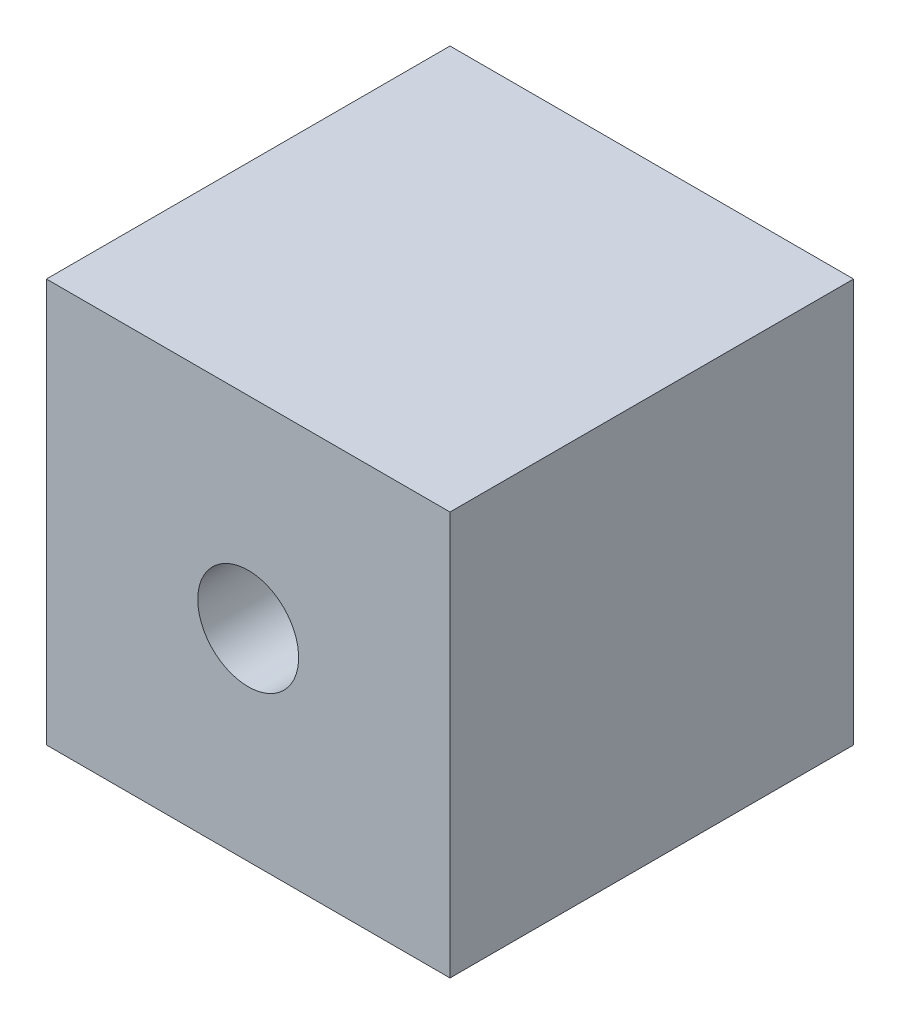
SolidWorks part; units mm, degrees
ref_plane "前视基准面" through (0, 0, 0) normal (0, 0, 1) x (1, 0, 0)
ref_plane "上视基准面" through (0, 0, 0) normal (0, 1, 0) x (1, 0, 0)
ref_plane "右视基准面" through (0, 0, 0) normal (1, 0, 0) x (0, 0, -1)
sketch "草图1" plane through (0, 0, 0) normal (0, 0, 1) x (1, 0, 0)
  line L1 (-30, 30) -> (30, 30)
  line L2 (-30, 30) -> (-30, -30)
  line L3 (-30, -30) -> (30, -30)
  line L4 (30, 30) -> (30, -30)
  line L5 (-30, 30) -> (30, -30) construction
  line L6 (-30, -30) -> (30, 30) construction
  point P0 (0, 0)
  dimension "D1" = 60
  dimension "D2" = 60
extrude "凸台-拉伸1" add sketch "草图1" along normal mid plane 60
sketch "草图2" plane through (0, 0, 30) normal (0, 0, -1) x (-1, 0, 0)
  circle A0 centre (0, 0) radius 7.5
  dimension "D1" = 15
extrude "切除-拉伸1" cut sketch "草图2" along normal through all
equation "\"零件重量\"= \"SW-质量\""
